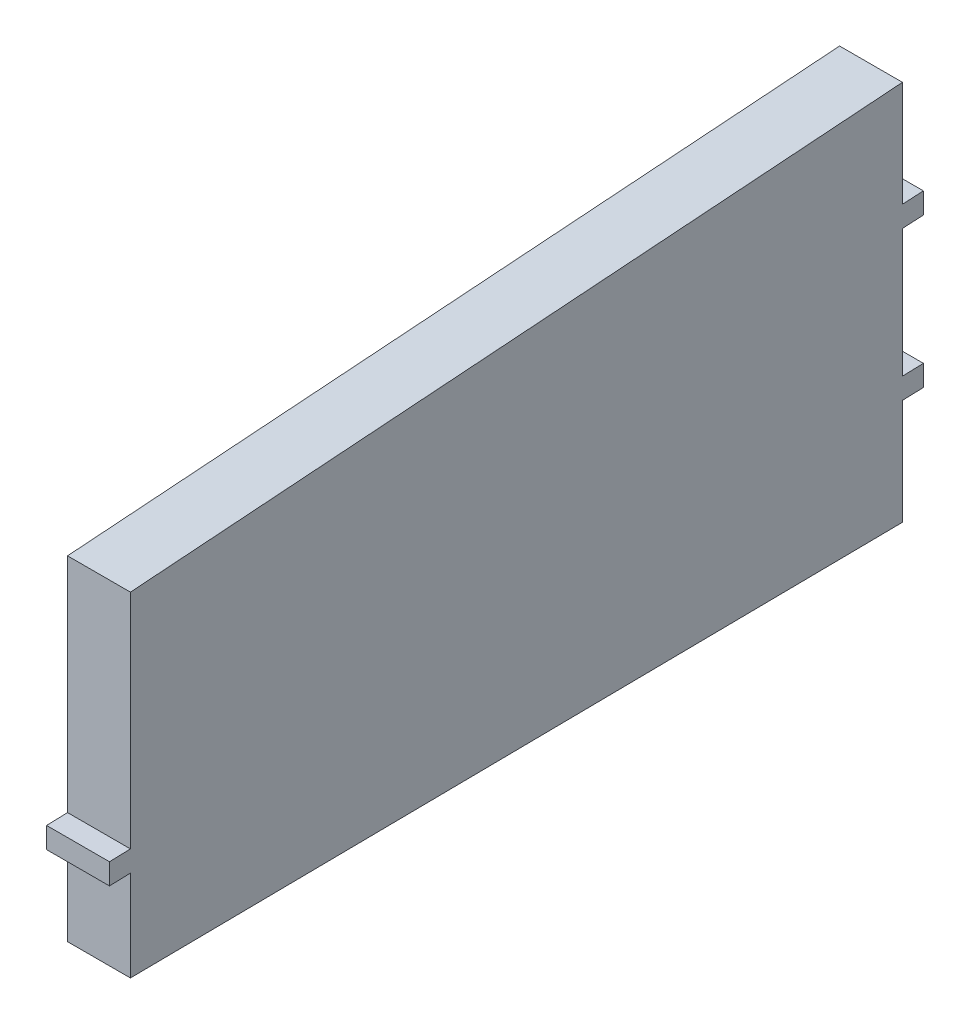
SolidWorks part; units mm, degrees
material "Balsa"
ref_plane "Front Plane" through (0, 0, 0) normal (0, 0, 1) x (1, 0, 0)
ref_plane "Top Plane" through (0, 0, 0) normal (0, 1, 0) x (1, 0, 0)
ref_plane "Right Plane" through (0, 0, 0) normal (1, 0, 0) x (0, 0, -1)
sketch "Sketch1" plane through (243.0177, 0, 0) normal (1, 0, 0) x (0, 0, -1)
  line L1 (-780.0562, 400.4117) -> (-776.8812, 400.5793) construction
  line L2 (-776.8812, 400.5793) -> (-776.8812, 403.7543) construction
  line L3 (-776.8812, 403.7543) -> (-780.0562, 403.5867) construction
  line L5 (-780.0562, 377.8585) -> (-776.8812, 377.9547) construction
  line L6 (-776.8812, 377.9547) -> (-776.8812, 381.1297) construction
  line L7 (-776.8812, 381.1297) -> (-780.0562, 381.0335) construction
  line L9 (-780.0562, 400.4117) -> (-776.8812, 400.5793)
  line L10 (-776.8812, 400.5793) -> (-776.8812, 403.7543)
  line L11 (-776.8812, 403.7543) -> (-780.0562, 403.5867)
  line L13 (-780.0562, 377.8585) -> (-776.8812, 377.9547)
  line L14 (-776.8812, 377.9547) -> (-776.8812, 381.1297)
  line L15 (-776.8812, 381.1297) -> (-780.0562, 381.0335)
  line L16 (-776.8812, 419.8105) -> (-780.0562, 419.5822) construction
  line L17 (-776.8812, 361.8985) -> (-780.0562, 361.863) construction
  line L18 (-776.8812, 419.8105) -> (-780.0562, 419.5822) construction
  line L19 (-776.8812, 361.8985) -> (-780.0562, 361.863) construction
  line L20 (-900.177, 374.2185) -> (-897.002, 374.3147) construction
  line L22 (-897.002, 377.4897) -> (-900.177, 377.3935) construction
  line L23 (-900.177, 377.3935) -> (-900.177, 374.2185) construction
  line L25 (-897.002, 394.2388) -> (-897.002, 397.4138) construction
  line L28 (-897.002, 360.554) -> (-900.177, 360.5185) construction
  line L29 (-897.002, 411.1745) -> (-900.177, 410.9462) construction
  line L30 (-900.177, 374.2185) -> (-897.002, 374.3147)
  line L32 (-897.002, 377.4897) -> (-900.177, 377.3935)
  line L33 (-900.177, 377.3935) -> (-900.177, 374.2185)
  line L35 (-897.002, 394.2388) -> (-897.002, 397.4138)
  line L38 (-897.002, 360.554) -> (-900.177, 360.5185) construction
  line L39 (-897.002, 411.1745) -> (-900.177, 410.9462) construction
  line L40 (-897.002, 411.1745) -> (-897.002, 397.4138)
  line L41 (-897.002, 394.2388) -> (-897.002, 377.4897)
  line L42 (-897.002, 374.3147) -> (-897.002, 360.554)
  line L43 (-897.002, 360.554) -> (-780.0562, 361.863)
  line L44 (-780.0562, 361.863) -> (-780.0562, 377.8585)
  line L45 (-780.0562, 381.0335) -> (-780.0562, 400.4117)
  line L46 (-780.0562, 403.5867) -> (-780.0562, 419.5822)
  line L47 (-780.0562, 419.5822) -> (-897.002, 411.1745)
extrude "Boss-Extrude1" add sketch "Sketch1" along normal up to surface (9.525 mm away)
